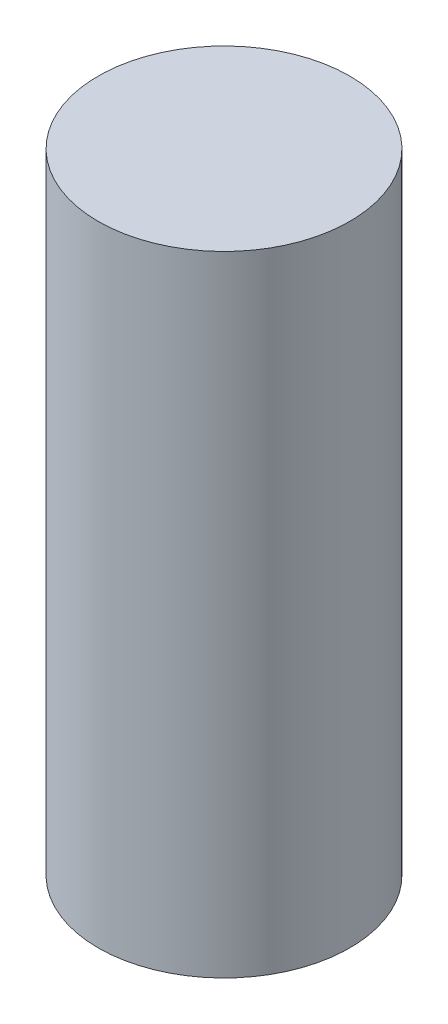
SolidWorks part; units mm, degrees
ref_plane "Ebene vorne" through (0, 0, 0) normal (0, 0, 1) x (1, 0, 0)
ref_plane "Ebene oben" through (0, 0, 0) normal (0, 1, 0) x (1, 0, 0)
ref_plane "Ebene rechts" through (0, 0, 0) normal (1, 0, 0) x (0, 0, -1)
sketch "Skizze1" plane through (0, 0, 0) normal (0, 1, 0) x (1, 0, 0)
  circle A0 centre (0, 0) radius 3
extrude "Aufsatz-Linear austragen1" add sketch "Skizze1" along normal blind 15
